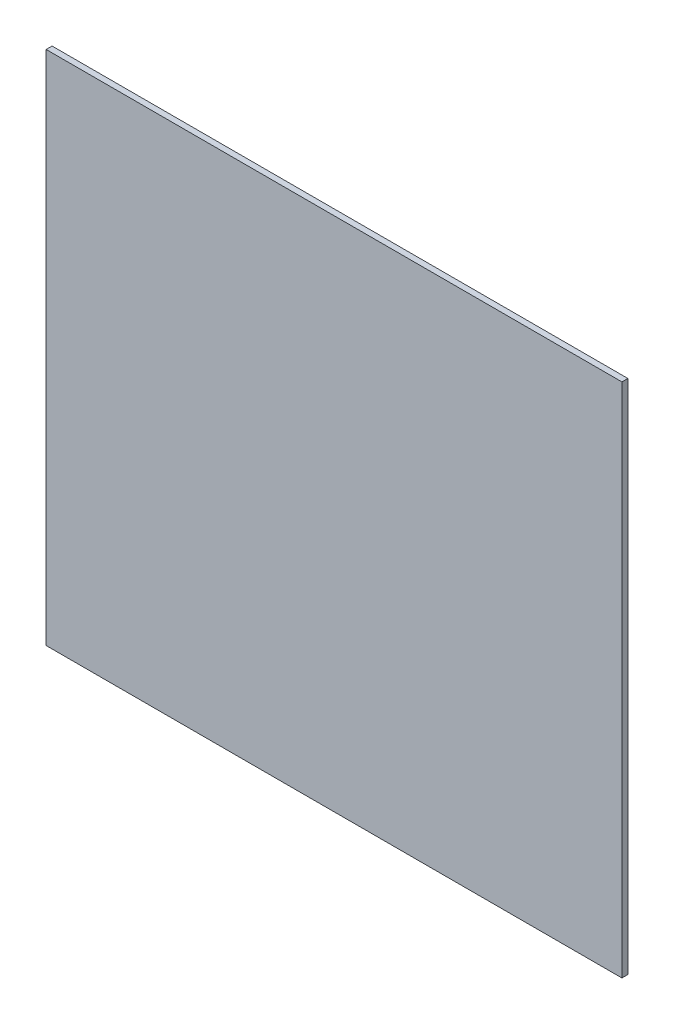
SolidWorks part; units mm, degrees
ref_plane "Спереди" through (0, 0, 0) normal (0, 0, 1) x (1, 0, 0)
ref_plane "Сверху" through (0, 0, 0) normal (0, 1, 0) x (1, 0, 0)
ref_plane "Справа" through (0, 0, 0) normal (1, 0, 0) x (0, 0, -1)
other "Configuration Table"
sketch "Эскиз1" plane through (0, 0, 0) normal (0, 0, 1) x (1, 0, 0)
  line L1 (145, 130) -> (-145, 130)
  line L2 (145, 130) -> (145, -130)
  line L3 (145, -130) -> (-145, -130)
  line L4 (-145, 130) -> (-145, -130)
  line L5 (145, 130) -> (-145, -130) construction
  line L6 (145, -130) -> (-145, 130) construction
  point P0 (0, 0)
  dimension "D1" = 260
  dimension "D2" = 290
extrude "Бобышка-Вытянуть1" add sketch "Эскиз1" along normal blind 3
